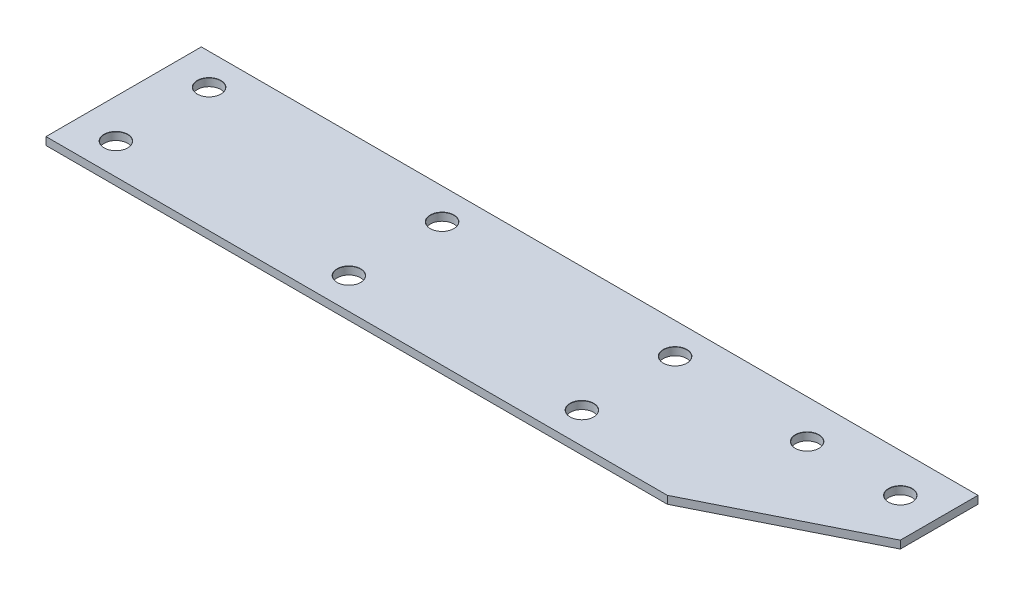
SolidWorks part; units mm, degrees
ref_plane "前视基准面" through (0, 0, 0) normal (0, 0, 1) x (1, 0, 0)
ref_plane "上视基准面" through (0, 0, 0) normal (0, 1, 0) x (1, 0, 0)
ref_plane "右视基准面" through (0, 0, 0) normal (1, 0, 0) x (0, 0, -1)
other "Configuration Table"
sketch "草图1" plane through (0, 0, 0) normal (0, 1, 0) x (1, 0, 0)
  line L0 (100, 10) -> (80, 0)
  line L1 (0, 0) -> (80, 0)
  line L2 (0, 0) -> (0, 20)
  line L3 (0, 20) -> (100, 20)
  line L4 (100, 10) -> (100, 20)
  dimension "D1" = 20
  dimension "D2" = 100
  dimension "D3" = 20
  dimension "D4" = 10
extrude "凸台-拉伸1" add sketch "草图1" along normal blind 1 contours L3 L4 L0 L1 L2
sketch "草图2" plane through (0, 1, 0) normal (0, 1, 0) x (1, 0, 0)
  line L0 (0, 0) -> (0, 20) construction
  line L1 (5, 16) -> (95, 16)
  line L2 (5, 16) -> (5, 4)
  line L3 (5, 4) -> (95, 4)
  line L4 (95, 16) -> (95, 4)
  line L5 (100, 10) -> (100, 20) construction
  line L6 (0, 20) -> (100, 20) construction
  point P10 (35, 16)
  point P11 (65, 16)
  point P12 (35, 4)
  point P13 (65, 4)
  dimension "D1" = 5
  dimension "D2" = 5
  dimension "D3" = 12
  dimension "D4" = 4
  dimension "D5" = 30
  dimension "D6" = 30
  dimension "D7" = 30
  dimension "D8" = 30
hole_wizard "Ø3.0mm 暗销孔1" positions "3D草图1" profile "草图3" hole size "Ø3.0" standard "GB" end condition through all
sketch3d "3D草图1"
  line L0 (0, 1, -20) -> (100, 1, -20) construction
  line L1 (100, 1, -10) -> (100, 1, -20) construction
  point P0 (5, 1, -16)
  point P3 (5, 1, -4)
  point P13 (35, 1, -16)
  point P16 (65, 1, -16)
  point P19 (35, 1, -4)
  point P22 (65, 1, -4)
  point P29 (83, 1, -15)
  point P31 (95, 1, -15)
  dimension "D1" = 12
  dimension "D2" = 5
  dimension "D3" = 5
  dimension "D4" = 5
sketch "草图3" plane through (5, 1, -16) normal (1, 0, 0) x (0, 0, 1)
  line L0 (0, 0) -> (0, 1)
  line L1 (0, 1) -> (1.5, 1)
  line L2 (1.5, 1) -> (1.5, 0.025)
  line L3 (1.5, 0.025) -> (1.525, 0)
  line L5 (1.525, 0) -> (0, 0)
  line L6 (-1.5, 0.025) -> (-1.525, 0) construction
  line L11 (0, -6.35) -> (0, 107.95) construction
  dimension "通孔孔直径" = 3
  dimension "通孔孔深度" = 1
  dimension "近端锥形沉头孔直径" = 3.05
  dimension "近端锥形沉头孔角度" = 90
